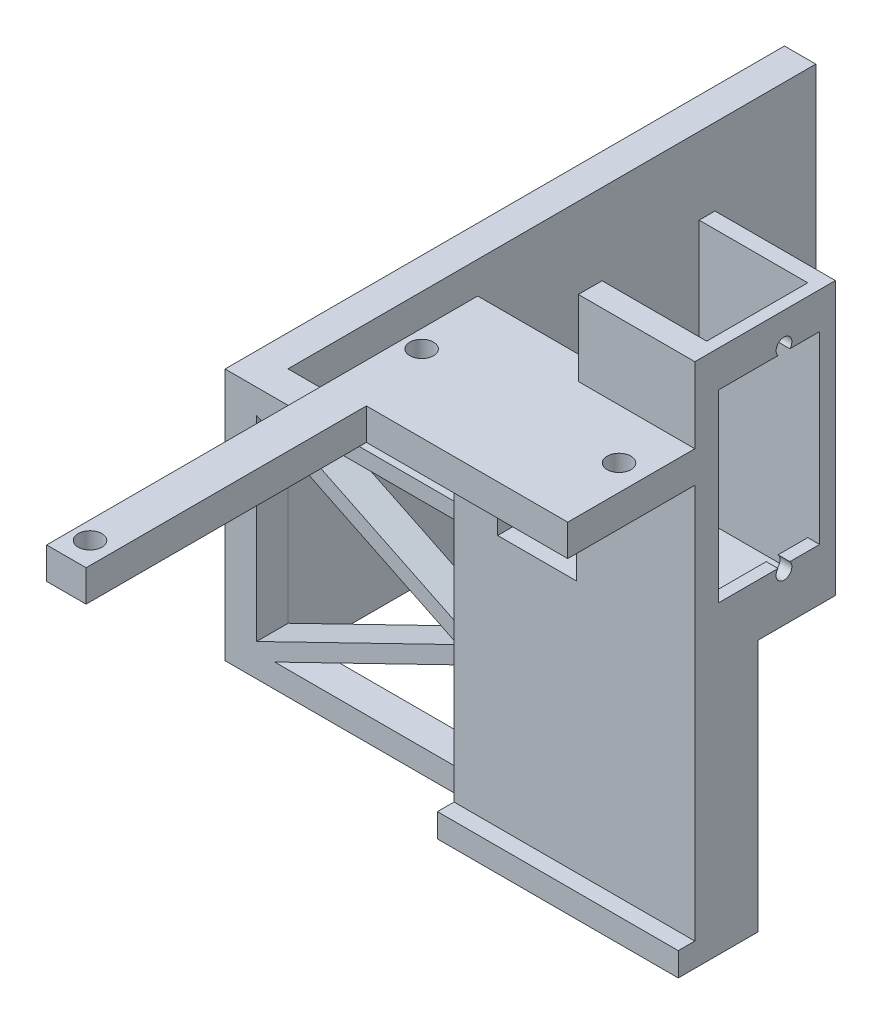
SolidWorks part; units mm, degrees
ref_plane "Front Plane" through (0, 0, 0) normal (0, 0, 1) x (1, 0, 0)
ref_plane "Top Plane" through (0, 0, 0) normal (0, 1, 0) x (1, 0, 0)
ref_plane "Right Plane" through (0, 0, 0) normal (1, 0, 0) x (0, 0, -1)
sketch "Sketch1" plane through (0, 0, 0) normal (0, 1, 0) x (1, 0, 0)
  line L1 (-41.2344, 16.8984) -> (-36.2344, 16.8984)
  line L2 (-41.2344, 16.8984) -> (-41.2344, -32.6016)
  line L3 (-41.2344, -32.6016) -> (-36.2344, -32.6016)
  line L4 (-36.2344, 16.8984) -> (-36.2344, -32.6016)
  line L5 (-36.2344, 16.8984) -> (-10.7344, 16.8984)
  line L6 (-36.2344, 16.8984) -> (-36.2344, 2.8984)
  line L7 (-36.2344, 2.8984) -> (-10.7344, 2.8984)
  line L8 (-10.7344, 16.8984) -> (-10.7344, 2.8984)
  dimension "D1" = 49.5
  dimension "D2" = 5
  dimension "D3" = 25.5
  dimension "D4" = 14
extrude "Boss-Extrude1" add sketch "Sketch1" along normal blind 4 contours L8 L5 L4 L7
sketch "Sketch2" plane through (0, 4, 0) normal (0, 1, 0) x (1, 0, 0)
  line L0 (-41.2344, -32.6016) -> (-36.2344, -32.6016) construction
  line L2 (-41.2344, 16.8984) -> (-10.7344, 16.8984) construction
  circle A0 centre (-38.9844, -29.3516) radius 1.5
  circle A1 centre (-38.9844, 12.6484) radius 1.5
  circle A2 centre (-13.9844, 12.6484) radius 1.5
  dimension "D1" = 3
  dimension "D3" = 3
  dimension "D4" = 4.25
  dimension "D5" = 3.25
  dimension "D6" = 4.25
  dimension "D7" = 3
  dimension "D8" = 25
extrude "Cut-Extrude1" cut sketch "Sketch2" against normal through all
sketch "Sketch3" plane through (0, 0, -16.8984) normal (0, 0, -1) x (-1, 0, 0)
  line L4 (10.7344, 0) -> (41.2344, 0)
  line L5 (41.2344, 0) -> (41.2344, 4)
  line L6 (41.2344, 4) -> (10.7344, 4)
  line L7 (10.7344, 4) -> (10.7344, 0)
  line L8 (10.7344, 0) -> (41.2344, 0)
  line L9 (41.2344, 0) -> (41.2344, 4)
  line L10 (41.2344, 4) -> (10.7344, 4)
  line L11 (10.7344, 4) -> (10.7344, 0)
  dimension "D1" = 0
extrude "Boss-Extrude2" add sketch "Sketch3" along normal blind 5.1
sketch "Sketch4" plane through (0, 0, 0) normal (0, -1, 0) x (1, 0, 0)
  line L0 (-41.2344, -21.9984) -> (-41.2344, 32.6016) construction
  line L1 (-10.7344, -21.9984) -> (-41.2344, -21.9984)
  line L2 (-10.7344, -21.9984) -> (-10.7344, -18.9984)
  line L3 (-10.7344, -18.9984) -> (-41.2344, -18.9984)
  line L4 (-41.2344, -21.9984) -> (-41.2344, -18.9984)
  dimension "D1" = 3
extrude "Boss-Extrude3" add sketch "Sketch4" along normal blind 21
sketch "Sketch5" plane through (0, 0, -21.9984) normal (0, 0, -1) x (-1, 0, 0)
  line L0 (10.7344, 4) -> (10.7344, -21) construction
  line L1 (10.7344, -19) -> (41.2344, -19)
  line L2 (10.7344, -19) -> (10.7344, -21)
  line L3 (10.7344, -21) -> (41.2344, -21)
  line L4 (41.2344, -19) -> (41.2344, -21)
  dimension "D1" = 2
extrude "Boss-Extrude8" add sketch "Sketch5" along normal blind 14.8 contours L1 L4 L3 L2
sketch "Sketch10" plane through (0, -19, 0) normal (0, 1, 0) x (1, 0, 0)
  line L0 (-10.7344, 36.7984) -> (-10.7344, 21.9984) construction
  line L1 (-41.2344, 36.7984) -> (-10.7344, 36.7984)
  line L2 (-41.2344, 36.7984) -> (-41.2344, 34.7984)
  line L3 (-41.2344, 34.7984) -> (-10.7344, 34.7984)
  line L4 (-10.7344, 36.7984) -> (-10.7344, 34.7984)
  dimension "D1" = 2
extrude "Boss-Extrude9" add sketch "Sketch10" along normal blind 16.8
sketch "Sketch11" plane through (0, -19, 0) normal (0, 1, 0) x (1, 0, 0)
  line L0 (-41.2344, 34.7984) -> (-10.7344, 34.7984) construction
  line L1 (-10.7344, 21.9984) -> (-12.2344, 21.9984)
  line L2 (-10.7344, 21.9984) -> (-10.7344, 34.7984)
  line L3 (-10.7344, 34.7984) -> (-12.2344, 34.7984)
  line L4 (-12.2344, 21.9984) -> (-12.2344, 34.7984)
  dimension "D1" = 1.5
extrude "Boss-Extrude10" add sketch "Sketch11" along normal blind 4.6
sketch "Sketch13" plane through (0, -2.2, 0) normal (0, 1, 0) x (1, 0, 0)
  line L0 (-41.2344, 34.7984) -> (-10.7344, 34.7984) construction
  line L1 (-10.7344, 36.7984) -> (-25.9844, 36.7984)
  line L2 (-10.7344, 36.7984) -> (-10.7344, 34.7984)
  line L3 (-10.7344, 34.7984) -> (-25.9844, 34.7984)
  line L4 (-25.9844, 36.7984) -> (-25.9844, 34.7984)
extrude "Boss-Extrude11" add sketch "Sketch13" along normal blind 15.75
ref_plane "Plane1" through (0, -2.725, 0) normal (0, -1, 0) x (-1, 0, 0)
sketch "Sketch14" plane through (0, 0, -18.9984) normal (0, 0, 1) x (1, 0, 0)
  line L0 (-10.7344, -21) -> (-41.2344, -21) construction
  line L1 (-35.7068, -13) -> (-25.7068, -13)
  line L2 (-35.7068, -13) -> (-35.7068, -18)
  line L3 (-35.7068, -18) -> (-25.7068, -18)
  line L4 (-25.7068, -13) -> (-25.7068, -18)
  dimension "D1" = 5
  dimension "D2" = 10
  dimension "D3" = 3
extrude "Cut-Extrude5" cut sketch "Sketch14" against normal blind 3
sketch "Sketch15" plane through (0, 4, 0) normal (0, 1, 0) x (1, 0, 0)
  line L1 (-10.7344, 21.9984) -> (-25.4844, 21.9984)
  line L2 (-10.7344, 21.9984) -> (-10.7344, 18.9984)
  line L3 (-10.7344, 18.9984) -> (-25.4844, 18.9984)
  line L4 (-25.4844, 21.9984) -> (-25.4844, 18.9984)
  dimension "D1" = 3
  dimension "D2" = 14.75
sketch "Sketch16" plane through (-10.7344, 0, 0) normal (1, 0, 0) x (0, 0, -1)
  line L0 (21.9984, -14.4) -> (34.7984, -14.4) construction
  circle A0 centre (30.2865, -15.0598) radius 1
  point P6 (28.3984, -14.4)
  dimension "D1" = 2
  dimension "D2" = 2
extrude "Cut-Extrude6" cut sketch "Sketch16" against normal blind 10
mirror "Mirror1" about plane through (0, -2.725, 0) normal (0, -1, 0) of "Boss-Extrude10", "Cut-Extrude6"
extrude "Boss-Extrude12" add sketch "Sketch15" along normal up to vertex (9.55 mm away) contours L3 L4 L1 L2
sketch "Sketch18" plane through (0, -21, 0) normal (0, -1, 0) x (1, 0, 0)
  line L0 (-10.7344, -36.7984) -> (-10.7344, -18.9984) construction
  line L1 (-41.2344, -18.9984) -> (-10.7344, -18.9984)
  line L2 (-41.2344, -18.9984) -> (-41.2344, -22.9984)
  line L3 (-41.2344, -22.9984) -> (-10.7344, -22.9984)
  line L4 (-10.7344, -18.9984) -> (-10.7344, -22.9984)
  dimension "D1" = 4
extrude "Boss-Extrude13" add sketch "Sketch18" along normal blind 32
sketch "Sketch19" plane through (0, 0, -18.9984) normal (0, 0, 1) x (1, 0, 0)
  line L0 (-10.7344, -53) -> (-10.7344, 0) construction
  line L1 (-41.2344, -53) -> (-10.7344, -53)
  line L2 (-41.2344, -53) -> (-41.2344, -50)
  line L3 (-41.2344, -50) -> (-10.7344, -50)
  line L4 (-10.7344, -53) -> (-10.7344, -50)
  dimension "D1" = 3
extrude "Boss-Extrude14" add sketch "Sketch19" along normal blind 2.1
sketch "Sketch20" plane through (0, 0, -22.9984) normal (0, 0, -1) x (-1, 0, 0)
  line L1 (14.7344, -23) -> (70.2344, -23)
  line L2 (14.7344, -23) -> (14.7344, -50)
  line L3 (14.7344, -50) -> (70.2344, -50)
  line L4 (70.2344, -23) -> (70.2344, -50)
  line L5 (41.2344, -21) -> (10.7344, -21) construction
  line L6 (10.7344, -50) -> (41.2344, -50) construction
  line L7 (41.2344, -53) -> (10.7344, -53) construction
  line L8 (14.7344, -23) -> (70.2344, -50) construction
  line L9 (14.7344, -50) -> (70.2344, -23) construction
  line L10 (17.0203, -50) -> (42.4844, -37.6121)
  line L11 (42.4844, -37.6121) -> (67.9485, -50)
  line L12 (70.2344, -48.8879) -> (44.7703, -36.5)
  line L13 (44.7703, -36.5) -> (70.2344, -24.1121)
  line L14 (67.9485, -23) -> (42.4844, -35.3879)
  line L15 (42.4844, -35.3879) -> (17.0203, -23)
  line L16 (14.7344, -24.1121) -> (40.1985, -36.5)
  line L17 (40.1985, -36.5) -> (14.7344, -48.8879)
  line L23 (10.7344, -21) -> (74.2344, -21)
  line L24 (10.7344, -21) -> (10.7344, -53)
  line L25 (10.7344, -53) -> (74.2344, -53)
  line L26 (74.2344, -21) -> (74.2344, -53)
  line M15 (41.2344, -21) -> (10.7344, -21)
  line M16 (10.7344, -21) -> (10.7344, -53)
  line M17 (10.7344, -53) -> (41.2344, -53)
  line M18 (41.2344, -53) -> (41.2344, -21)
  dimension "D2" = 2
  dimension "D3" = 4
  dimension "D4" = 4
  dimension "D5" = 1
  dimension "D6" = 1
  dimension "D7" = 1
  dimension "D8" = 1
  dimension "D9" = 63.5
extrude "Boss-Extrude17" add sketch "Sketch20" along normal blind 4 contours L3 L2 L1 M18 M15 M16 M17 | L26 L23 L1 L4 L3 L25 M18 | L16 L17 L2 L3 L10 L15 L1 M18 | L14 L15 L10 L11 L3 L4 L12 L13 L1 M18
sketch "Sketch24" plane through (0, 0, -26.9984) normal (0, 0, -1) x (-1, 0, 0)
  line L0 (10.7344, -53) -> (74.2344, -53) construction
  line L1 (74.2344, -21) -> (70.2651, -21)
  line L2 (74.2344, -21) -> (74.2344, -53)
  line L3 (74.2344, -53) -> (70.2651, -53)
  line L4 (70.2651, -21) -> (70.2651, -53)
extrude "Boss-Extrude18" add sketch "Sketch24" along normal blind 66.85
sketch "Sketch26" plane through (-70.2651, 0, 0) normal (1, 0, 0) x (0, 0, -1)
  line L0 (26.9984, -21) -> (26.9984, -53) construction
  line L1 (26.9984, -23) -> (89.8484, -23)
  line L2 (26.9984, -23) -> (26.9984, -51)
  line L3 (26.9984, -51) -> (89.8484, -51)
  line L4 (89.8484, -23) -> (89.8484, -51)
  line L5 (93.8484, -53) -> (26.9984, -53) construction
  line L6 (93.8484, -21) -> (93.8484, -53) construction
  line L7 (93.8484, -21) -> (26.9984, -21) construction
  dimension "D1" = 2
  dimension "D2" = 4
  dimension "D3" = 2
